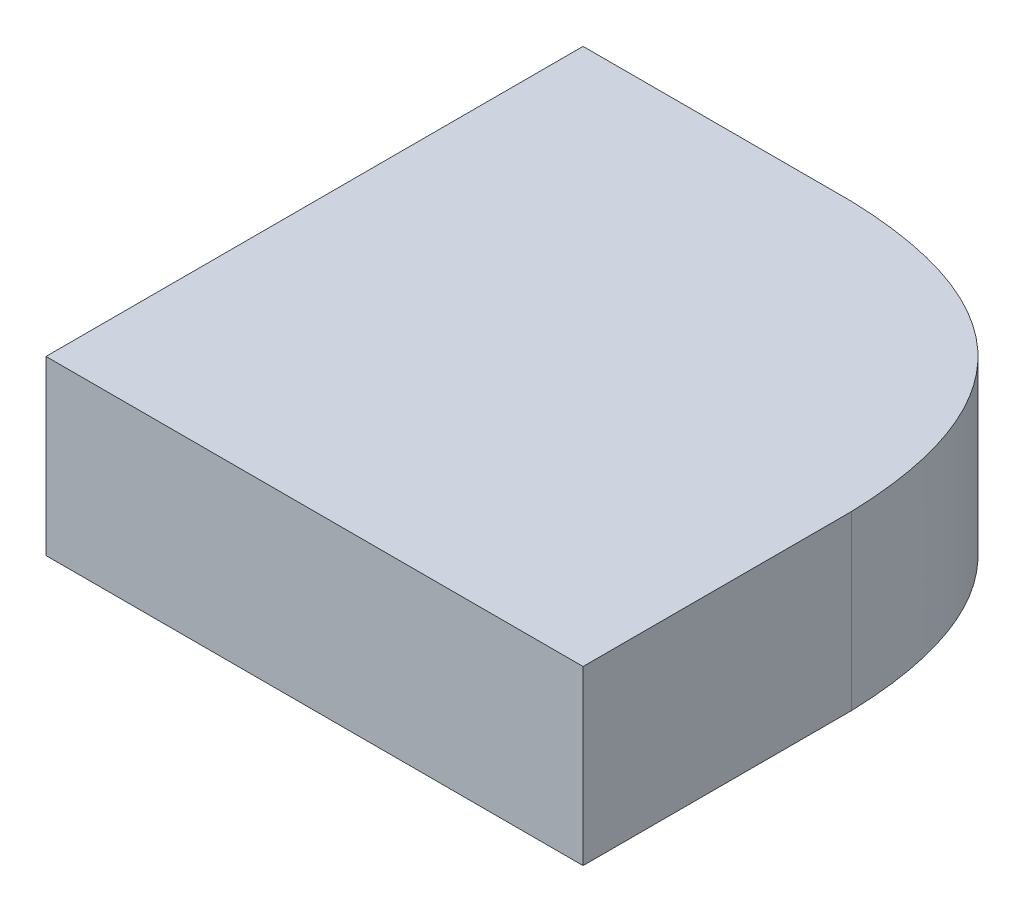
SolidWorks part; units mm, degrees
ref_plane "Front Plane" through (0, 0, 0) normal (0, 0, 1) x (1, 0, 0)
ref_plane "Top Plane" through (0, 0, 0) normal (0, 1, 0) x (1, 0, 0)
ref_plane "Right Plane" through (0, 0, 0) normal (1, 0, 0) x (0, 0, -1)
sketch "Sketch1" plane through (0, 0, 0) normal (0, 1, 0) x (1, 0, 0)
  line L3 (0, 12.4558) -> (-12.4558, 12.4558)
  line L4 (12.4558, 0) -> (12.4558, -12.4558)
  line L5 (12.4558, -12.4558) -> (-12.4558, -12.4558)
  line L6 (-12.4558, -12.4558) -> (-12.4558, 12.4558)
  spline S0 degree 2 poles (0, 12.4558) (12.0918, 12.0918) (12.4558, 0) knots 0 0 0 1 1 1
extrude "Boss-Extrude1" add sketch "Sketch1" along normal blind 8
